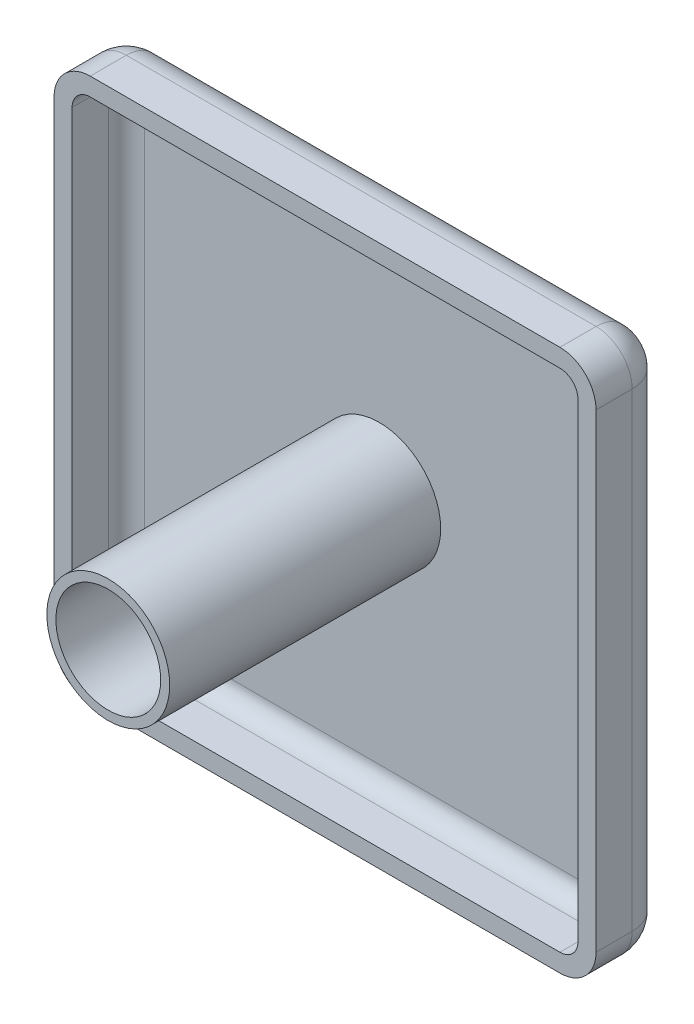
SolidWorks part; units mm, degrees
ref_plane "前视基准面" through (0, 0, 0) normal (0, 0, 1) x (1, 0, 0)
ref_plane "上视基准面" through (0, 0, 0) normal (0, 1, 0) x (1, 0, 0)
ref_plane "右视基准面" through (0, 0, 0) normal (1, 0, 0) x (0, 0, -1)
sketch "草图1" plane through (0, 0, 0) normal (0, 0, 1) x (1, 0, 0)
  line L1 (-15, 15) -> (15, 15)
  line L2 (-15, 15) -> (-15, -15)
  line L3 (-15, -15) -> (15, -15)
  line L4 (15, 15) -> (15, -15)
  line L5 (-15, 15) -> (15, -15) construction
  line L6 (-15, -15) -> (15, 15) construction
  point P0 (0, 0)
  dimension "D1" = 30
  dimension "D2" = 30
extrude "凸台-拉伸1" add sketch "草图1" along normal blind 4
fillet "圆角1" radius 2 8 edges at (0, 15, 0) (-15, 0, 0) (0, -15, 0) (15, 0, 0) (-15, -15, 2) (15, -15, 2) (15, 15, 2) (-15, 15, 2)
shell "抽壳1" thickness 1
sketch "草图2" plane through (0, 0, 1) normal (0, 0, 1) x (1, 0, 0)
  circle A0 centre (0, 0) radius 3.4
  dimension "D1" = 6.8
extrude "凸台-拉伸2" add sketch "草图2" along normal blind 15
sketch "草图3" plane through (0, 0, 16) normal (0, 0, 1) x (1, 0, 0)
  circle A1 centre (0, 0) radius 2.9
extrude "切除-拉伸1" cut sketch "草图3" against normal up to surface (15 mm away) up to face at (0, 0, 1)
